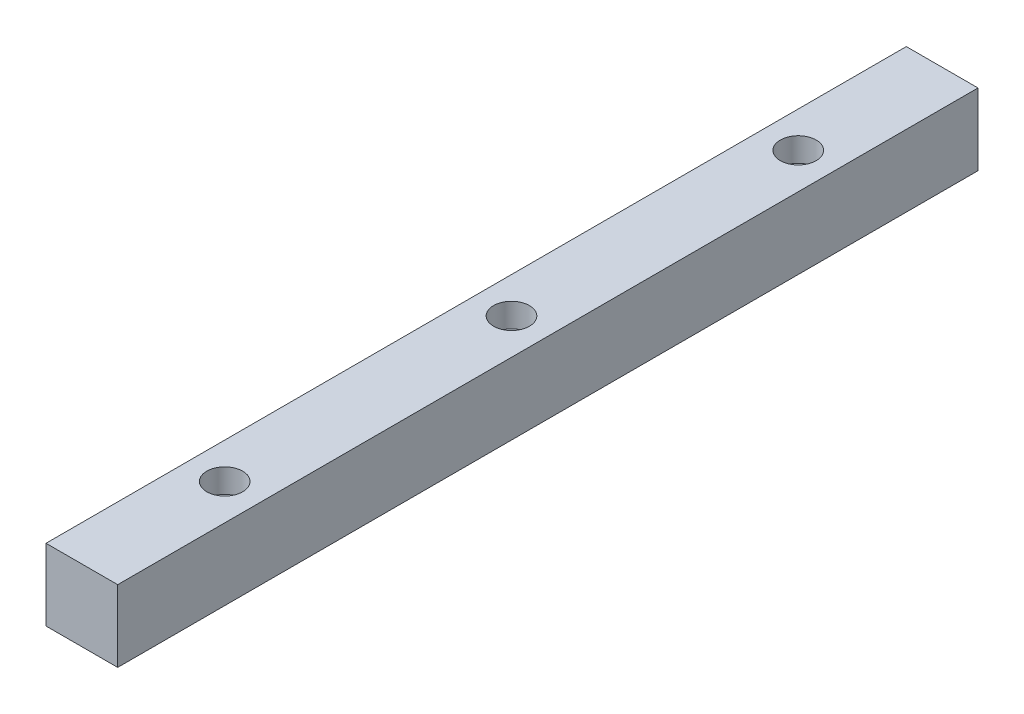
SolidWorks part; units mm, degrees
ref_plane "Спереди" through (0, 0, 0) normal (0, 0, 1) x (1, 0, 0)
ref_plane "Сверху" through (0, 0, 0) normal (0, 1, 0) x (1, 0, 0)
ref_plane "Справа" through (0, 0, 0) normal (1, 0, 0) x (0, 0, -1)
sketch "Эскиз1" plane through (0, 0, 0) normal (0, 1, 0) x (1, 0, 0)
  line L0 (-55.0551, 279.2191) -> (-55.0551, -80.7809) construction
  line L2 (-62.5551, 249.3223) -> (-62.5551, 69.3223)
  line L3 (-62.5551, 69.3223) -> (-47.5551, 69.3223)
  line L4 (-47.5551, 249.3223) -> (-47.5551, 69.3223)
  line L6 (-62.5551, 249.3223) -> (-47.5551, 249.3223)
  circle A1 centre (-55.0551, 219.2191) radius 2
  circle A2 centre (-55.0551, 159.2191) radius 2
  circle A3 centre (-55.0551, 99.2191) radius 2
  dimension "D3" = 15
  dimension "D4" = 4
  dimension "D6" = 4
  dimension "D7" = 4
  dimension "D8" = 60
  dimension "D9" = 60
  dimension "D1" = 180
  dimension "D2" = 7.5
extrude "Бобышка-Вытянуть1" add sketch "Эскиз1" along normal blind 15
sketch "Эскиз2" plane through (0, 15, 0) normal (0, 1, 0) x (1, 0, 0)
  circle A2 centre (-55.0551, 99.2191) radius 3.75
  circle A3 centre (-55.0551, 159.2191) radius 3.75
  circle A4 centre (-55.0551, 219.2191) radius 3.75
  dimension "D1" = 7.5
  dimension "D2" = 7.5
  dimension "D3" = 7.5
extrude "Вырез-Вытянуть1" cut sketch "Эскиз2" against normal blind 5
